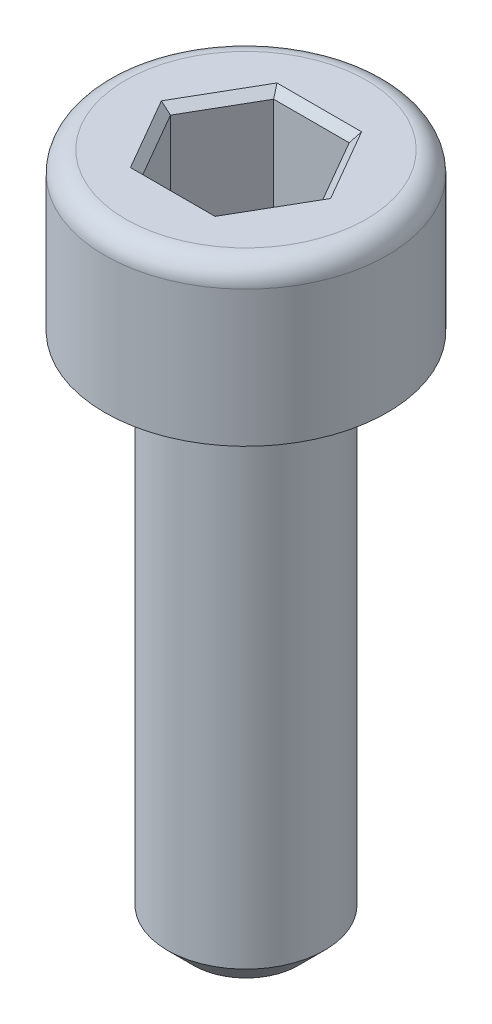
SolidWorks part; units mm, degrees
material "AISI Acier inoxydable type 316L"
ref_plane "Plan de face" through (0, 0, 0) normal (0, 0, 1) x (1, 0, 0)
ref_plane "Plan de dessus" through (0, 0, 0) normal (0, 1, 0) x (1, 0, 0)
ref_plane "Plan de droite" through (0, 0, 0) normal (1, 0, 0) x (0, 0, -1)
sketch "Esquisse1" plane through (0, 0, 0) normal (0, 0, 1) x (1, 0, 0)
  line L0 (0, 6.973) -> (0, -16.342) construction
  line L1 (1.5, -9.5) -> (1, -10)
  line L2 (0, 3) -> (2.3, 3)
  line L3 (2.7, 2.6) -> (2.7, 0)
  line L4 (2.7, 0) -> (1.5, 0)
  line L5 (1.5, 0) -> (1.5, -9.5)
  line L7 (1, -10) -> (0, -10)
  line L8 (0, -10) -> (0, 3)
  arc A0 (2.3, 3) -> (2.7, 2.6) centre (2.3, 2.6) cw
  point P9 (1.5, -10)
  point P13 (2.7, 3)
  dimension "D5" = 0.4
  dimension "D1" = 3
  dimension "D2" = 5.4
  dimension "D3" = 3
  dimension "D4" = 10
revolve "Révolution1" add sketch "Esquisse1" angle 360 about L0
cosmetic thread "Représentation de filetage1" parameters "D2"=2.439
sketch "Esquisse2" plane through (0, 3, 0) normal (0, 1, 0) x (1, 0, 0)
  line L0 (-1.4434, 0) -> (-0.7217, -1.25)
  line L1 (1.4434, 0) -> (0.7217, 1.25)
  line L2 (0.7217, 1.25) -> (-0.7217, 1.25)
  line L3 (-0.7217, 1.25) -> (-1.4434, 0)
  line L4 (-0.7217, -1.25) -> (0.7217, -1.25)
  line L5 (0.7217, -1.25) -> (1.4434, 0)
  circle A0 centre (0, 0) radius 1.25 construction
  dimension "D1" = 2.5
extrude "Enlèv. mat.-Extru.1" cut sketch "Esquisse2" against normal blind 2
chamfer "Chanfrein1" distance 0.15 angle 45 6 edges at (-1.0825, 3, -0.625) (-1.0825, 3, 0.625) (0, 3, 1.25) (1.0825, 3, 0.625) (1.0825, 3, -0.625) (0, 3, -1.25)
